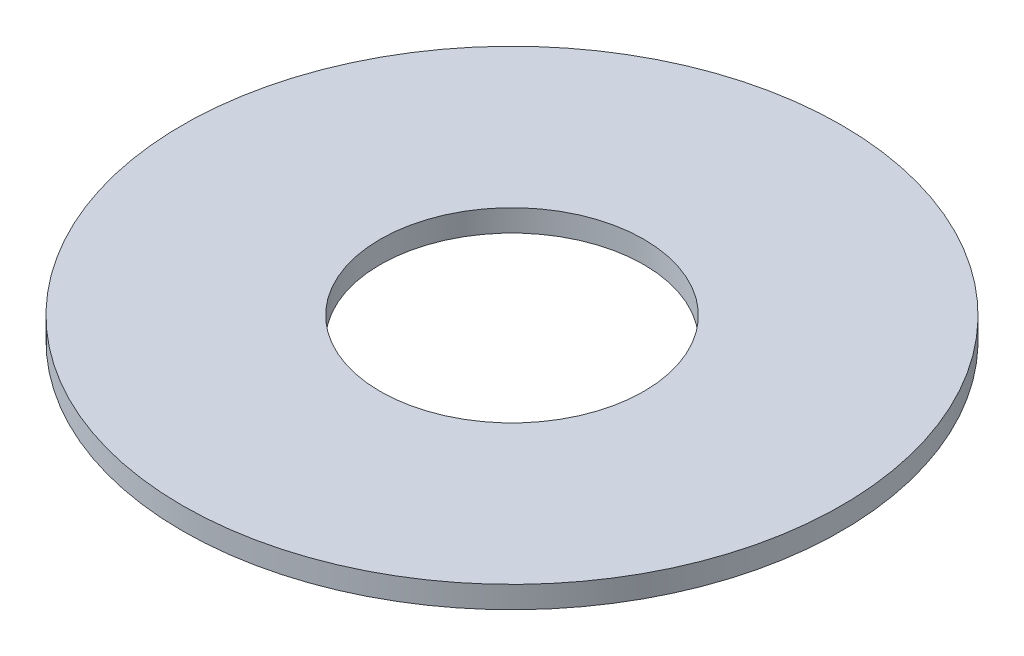
SolidWorks part; units mm, degrees
material "Nylon 6/10"
ref_plane "Front Plane" through (0, 0, 0) normal (0, 0, 1) x (1, 0, 0)
ref_plane "Top Plane" through (0, 0, 0) normal (0, 1, 0) x (1, 0, 0)
ref_plane "Right Plane" through (0, 0, 0) normal (1, 0, 0) x (0, 0, -1)
sketch "Sketch1" plane through (0, 0, 0) normal (0, 1, 0) x (1, 0, 0)
  circle A0 centre (0, 0) radius 19.05
  circle A1 centre (0, 0) radius 7.62
  dimension "D1" = 15.24
  dimension "D2" = 38.1
extrude "Boss-Extrude1" add sketch "Sketch1" along normal blind 1.27
